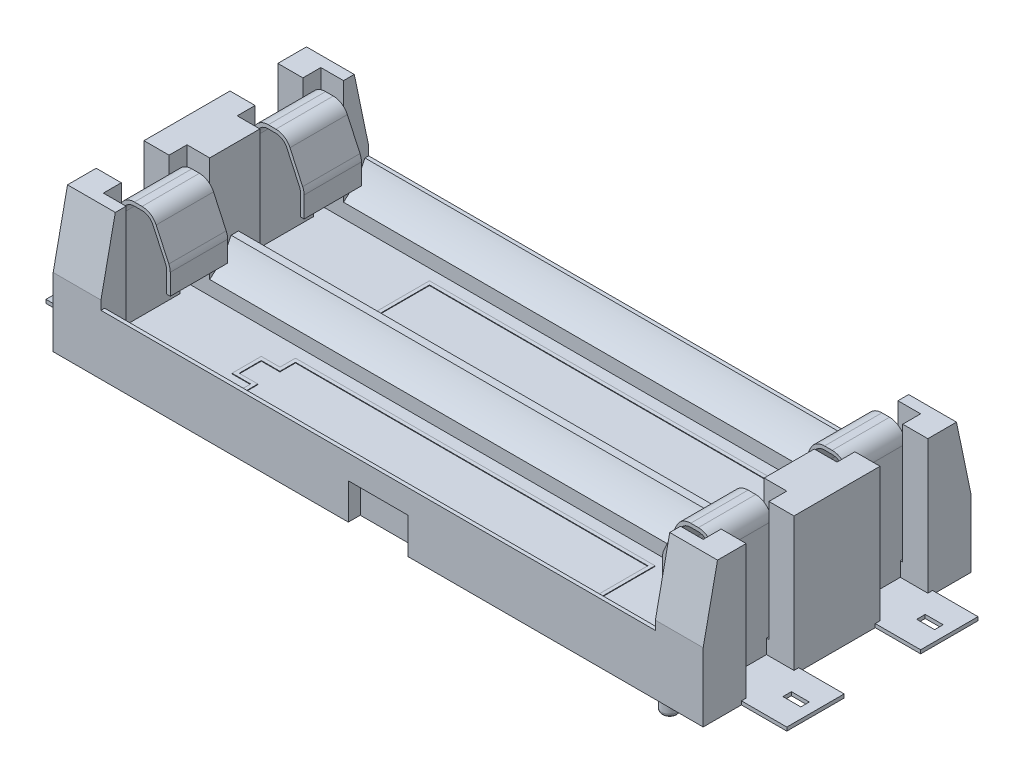
SolidWorks part; units mm, degrees
material "POM 乙缩醛共聚物"
ref_plane "Front" through (0, 0, 0) normal (0, 0, 1) x (1, 0, 0)
ref_plane "Top" through (0, 0, 0) normal (0, 1, 0) x (1, 0, 0)
ref_plane "Right" through (0, 0, 0) normal (1, 0, 0) x (0, 0, -1)
sketch "草图1" plane through (0, 0, 0) normal (0, 1, 0) x (1, 0, 0)
  line L1 (-27.2, -11.2) -> (27.2, -11.2)
  line L2 (-27.2, -11.2) -> (-27.2, 11.2)
  line L3 (-27.2, 11.2) -> (27.2, 11.2)
  line L4 (27.2, -11.2) -> (27.2, 11.2)
  line L5 (-27.2, -11.2) -> (27.2, 11.2) construction
  line L6 (-27.2, 11.2) -> (27.2, -11.2) construction
  point P0 (0, 0)
  dimension "D1" = 22.4
  dimension "D2" = 54.4
extrude "凸台-拉伸1" add sketch "草图1" along normal blind 11.5
ref_plane "基准面1" through (0, 5, 0) normal (0, 1, 0) x (1, 0, 0)
sketch "草图2" plane through (0, 5, 0) normal (0, 1, 0) x (1, 0, 0)
  line L1 (-23.2, -25.6311) -> (23.2, -25.6311)
  line L2 (-23.2, -25.6311) -> (-23.2, 25.6311)
  line L3 (-23.2, 25.6311) -> (23.2, 25.6311)
  line L4 (23.2, -25.6311) -> (23.2, 25.6311)
  line L5 (-23.2, -25.6311) -> (23.2, 25.6311) construction
  line L6 (-23.2, 25.6311) -> (23.2, -25.6311) construction
  point P0 (0, 0)
  dimension "D1" = 46.4
extrude "切除-拉伸1" cut sketch "草图2" along normal blind 11.4
sketch "草图3" plane through (0, 11.5, 0) normal (0, 1, 0) x (1, 0, 0)
  line L0 (-33.3126, 0) -> (0, 0) construction
  line L1 (0, 0) -> (0, 25.9446) construction
  line L2 (-23.2, 0) -> (-23.2, 11.2) construction
  line L3 (-23.2, 11.2) -> (-23.2, -11.2) construction
  line L4 (-27.2, 11.2) -> (-27.2, -11.2) construction
  line L5 (-21.3, 2.1) -> (-25.1, 2.1)
  line L6 (-21.3, 2.1) -> (-21.3, 9.1)
  line L7 (-21.3, 9.1) -> (-25.1, 9.1)
  line L8 (-25.1, 2.1) -> (-25.1, 3.6)
  line L9 (-21.3, 2.1) -> (-25.1, 9.1) construction
  line L10 (-21.3, 9.1) -> (-25.1, 2.1) construction
  line L11 (-25.1, 3.6) -> (-27.2, 3.6)
  line L14 (-27.2, 3.6) -> (-27.2, 7.6)
  line L15 (-23.2, 3.7905) -> (-27.2, 7.6) construction
  line L16 (-23.2, 7.4095) -> (-27.2, 3.6) construction
  line L17 (-25.1, 7.6) -> (-25.1, 9.1)
  line L18 (-25.1, 7.6) -> (-27.2, 7.6)
  line L19 (23.2, 7.4095) -> (27.2, 3.6) construction
  line L20 (23.2, 3.7905) -> (27.2, 7.6) construction
  line L21 (21.3, 9.1) -> (25.1, 2.1) construction
  line L22 (21.3, 2.1) -> (25.1, 9.1) construction
  line L23 (25.1, 7.6) -> (27.2, 7.6)
  line L24 (25.1, 7.6) -> (25.1, 9.1)
  line L25 (27.2, 3.6) -> (27.2, 7.6)
  line L26 (25.1, 3.6) -> (27.2, 3.6)
  line L27 (25.1, 2.1) -> (25.1, 3.6)
  line L28 (21.3, 9.1) -> (25.1, 9.1)
  line L29 (21.3, 2.1) -> (21.3, 9.1)
  line L30 (21.3, 2.1) -> (25.1, 2.1)
  line L31 (21.3, -2.1) -> (25.1, -9.1) construction
  line L32 (21.3, -9.1) -> (25.1, -2.1) construction
  line L33 (23.2, -3.7905) -> (27.2, -7.6) construction
  line L34 (23.2, -7.4095) -> (27.2, -3.6) construction
  line L35 (-23.2, -7.4095) -> (-27.2, -3.6) construction
  line L36 (-23.2, -3.7905) -> (-27.2, -7.6) construction
  line L37 (-21.3, -9.1) -> (-25.1, -2.1) construction
  line L38 (-21.3, -2.1) -> (-25.1, -9.1) construction
  line L39 (21.3, -2.1) -> (25.1, -2.1)
  line L40 (21.3, -2.1) -> (21.3, -9.1)
  line L41 (21.3, -9.1) -> (25.1, -9.1)
  line L42 (25.1, -2.1) -> (25.1, -3.6)
  line L43 (25.1, -3.6) -> (27.2, -3.6)
  line L44 (27.2, -3.6) -> (27.2, -7.6)
  line L45 (25.1, -7.6) -> (25.1, -9.1)
  line L46 (25.1, -7.6) -> (27.2, -7.6)
  line L47 (-25.1, -7.6) -> (-27.2, -7.6)
  line L48 (-25.1, -7.6) -> (-25.1, -9.1)
  line L49 (-27.2, -3.6) -> (-27.2, -7.6)
  line L50 (-25.1, -3.6) -> (-27.2, -3.6)
  line L51 (-25.1, -2.1) -> (-25.1, -3.6)
  line L52 (-21.3, -9.1) -> (-25.1, -9.1)
  line L53 (-21.3, -2.1) -> (-21.3, -9.1)
  line L54 (-21.3, -2.1) -> (-25.1, -2.1)
  point P9 (-23.2, 5.6)
  point P14 (-25.1, 5.6)
  point P33 (25.1, 5.6)
  point P34 (23.2, 5.6)
  point P55 (23.2, -5.6)
  point P56 (25.1, -5.6)
  point P57 (-25.1, -5.6)
  point P58 (-23.2, -5.6)
  dimension "D1" = 4
  dimension "D2" = 7
  dimension "D3" = 2.1
extrude "切除-拉伸2" cut sketch "草图3" against normal blind 10
sketch "草图4" plane through (-27.2, 0, 0) normal (-1, 0, 0) x (0, 0, 1)
  line L0 (0, 0) -> (0, 22.657) construction
  line L1 (-10, 11.5) -> (-11.2, 5.75)
  line L2 (-11.2, 11.5) -> (-7.6, 11.5) construction
  line L3 (-11.2, 11.5) -> (-11.2, 0) construction
  line L4 (-11.2, 5.75) -> (-14.7755, 5.75)
  line L5 (-14.7755, 5.75) -> (-14.7755, 11.5)
  line L6 (-14.7755, 11.5) -> (-10, 11.5)
  line L7 (14.7755, 11.5) -> (10, 11.5)
  line L8 (14.7755, 5.75) -> (14.7755, 11.5)
  line L9 (11.2, 5.75) -> (14.7755, 5.75)
  line L10 (10, 11.5) -> (11.2, 5.75)
  dimension "D1" = 10
extrude "切除-拉伸3" cut sketch "草图4" against normal through all
sketch "草图5" plane through (0, 1.5, 0) normal (0, 1, 0) x (1, 0, 0)
  line L0 (0, 23.9067) -> (0, 0) construction
  line L1 (0, 0) -> (-42.8753, 0) construction
  line L2 (24.6, 7.6) -> (24.6, 3.6)
  line L3 (-27.2, 7.6) -> (-24.6, 7.6)
  line L4 (-27.2, 7.6) -> (-27.2, 3.6)
  line L5 (-27.2, 3.6) -> (-24.6, 3.6)
  line L6 (-24.6, 7.6) -> (-24.6, 3.6)
  line L7 (27.2, 3.6) -> (24.6, 3.6)
  line L8 (27.2, 7.6) -> (27.2, 3.6)
  line L9 (27.2, 7.6) -> (24.6, 7.6)
  line L10 (27.2, -7.6) -> (24.6, -7.6)
  line L11 (27.2, -7.6) -> (27.2, -3.6)
  line L12 (27.2, -3.6) -> (24.6, -3.6)
  line L13 (-24.6, -7.6) -> (-24.6, -3.6)
  line L14 (-27.2, -3.6) -> (-24.6, -3.6)
  line L15 (-27.2, -7.6) -> (-27.2, -3.6)
  line L16 (-27.2, -7.6) -> (-24.6, -7.6)
  line L17 (24.6, -7.6) -> (24.6, -3.6)
  dimension "D1" = 2.6
extrude "切除-拉伸4" cut sketch "草图5" against normal blind 10
sketch "草图6" plane through (0, 1.5, 0) normal (0, 1, 0) x (1, 0, 0)
  line L0 (-21.3, 9.1) -> (-25.1, 9.1) construction
  line L1 (-21.8806, 9.1) -> (22.25, 9.1)
  line L2 (-21.8806, 9.1) -> (-21.8806, 2.1)
  line L3 (-21.8806, 2.1) -> (22.25, 2.1)
  line L4 (22.25, 9.1) -> (22.25, 2.1)
  line L5 (23.2, 2.1) -> (21.3, 2.1) construction
  line L6 (-23.2, -2.1) -> (-21.3, -2.1) construction
  line L7 (-22.25, -2.1) -> (22.25, -2.1)
  line L8 (-22.25, -2.1) -> (-22.25, -9.1)
  line L9 (-22.25, -9.1) -> (22.25, -9.1)
  line L10 (22.25, -2.1) -> (22.25, -9.1)
  line L11 (23.2, -9.1) -> (21.3, -9.1) construction
extrude "切除-拉伸5" cut sketch "草图6" along normal blind 10
sketch "草图7" plane through (0, 0, 0) normal (1, 0, 0) x (0, 0, -1)
  line L0 (-5.6, 1.5) -> (-5.6, 15.9161) construction
  line L1 (-7.6, 1.5) -> (-3.6, 1.5) construction
  line L2 (0, 0) -> (0, -3.0927) construction
  arc A0 (0, 8.5548) -> (0, 5.9452) centre (-5.6, 7.25) ccw
  circle A1 centre (-5.6, 7.25) radius 5.115 construction
  arc A2 (0, 8.5548) -> (0, 5.9452) centre (5.6, 7.25) cw
  dimension "D1" = 10.23
  dimension "D2" = 11.5
extrude "切除-拉伸6" cut sketch "草图7" against normal mid plane 46.4
sketch "草图8" plane through (0, 1.5, 0) normal (0, 1, 0) x (1, 0, 0)
  line L0 (-24.6, 5.6) -> (24.6, 5.6) construction
  line L1 (-24.6, 3.6) -> (-24.6, 7.6) construction
  line L2 (24.6, 7.6) -> (24.6, 3.6) construction
ref_plane "基准面2" through (0, 0, -5.6) normal (0, 0, 1) x (1, 0, 0)
sketch "草图9" plane through (0, 0, -5.6) normal (0, 0, 1) x (1, 0, 0)
  line L0 (-31, 0) -> (-24.6, 0)
  line L1 (-24.6, 0) -> (-24.6, 9.7542)
  line L2 (-23.6, 10.7542) -> (-22.9601, 10.7542)
  line L3 (-22.0522, 10.1735) -> (-20.9922, 7.8785)
  line L4 (-20.9, 7.4591) -> (-20.9, 5.7205)
  line L5 (-27.2, 0) -> (-27.2, 11.5) construction
  line L6 (-31, 0.3) -> (-24.9, 0.3)
  line L7 (-24.9, 0.3) -> (-24.9, 9.7542)
  line L8 (-23.6, 11.0542) -> (-22.9601, 11.0542)
  line L9 (-21.7799, 10.2993) -> (-20.7198, 8.0043)
  line L10 (-20.6, 7.4591) -> (-20.6, 5.7205)
  line L11 (-23.2, 2.6879) -> (-23.2, 11.5) construction
  line L12 (-20.9, 5.7205) -> (-20.6, 5.7205)
  line L13 (-20.6, 7.4591) -> (-20.6, 4.8223) construction
  line L14 (-20.9, 7.4591) -> (-20.9, 4.8223) construction
  line L15 (-31, 0.3) -> (-31, 0)
  arc A0 (-20.9, 7.4591) -> (-20.9922, 7.8785) centre (-21.9, 7.4591) ccw
  arc A1 (-24.6, 9.7542) -> (-23.6, 10.7542) centre (-23.6, 9.7542) cw
  arc A2 (-22.0522, 10.1735) -> (-22.9601, 10.7542) centre (-22.9601, 9.7542) ccw
  arc A3 (-24.9, 9.7542) -> (-23.6, 11.0542) centre (-23.6, 9.7542) cw
  arc A4 (-21.7799, 10.2993) -> (-22.9601, 11.0542) centre (-22.9601, 9.7542) ccw
  arc A5 (-20.6, 7.4591) -> (-20.7198, 8.0043) centre (-21.9, 7.4591) ccw
  point P27 (-20.9, 6.5898)
  dimension "D1" = 1
  dimension "D2" = 3.8
  dimension "D4" = 2.3
  dimension "D3" = 0.3
extrude "凸台-拉伸2" add sketch "草图9" along normal mid plane 4.8 separate body
sketch "草图10" plane through (0, 0.3, 0) normal (0, 1, 0) x (1, 0, 0)
  line L0 (-31, 5.6) -> (-24.9913, 5.6) construction
  line L1 (-31, 3.2) -> (-31, 8) construction
  line L2 (-27.06, 5.6) -> (27.06, 5.6) construction
  line L4 (-30.1262, 5.2434) -> (-28.6276, 5.2434)
  line L5 (-30.1262, 5.2434) -> (-30.1262, 5.9566)
  line L6 (-30.1262, 5.9566) -> (-28.6276, 5.9566)
  line L7 (-28.6276, 5.2434) -> (-28.6276, 5.9566)
  line L8 (-30.1262, 5.2434) -> (-28.6276, 5.9566) construction
  line L9 (-30.1262, 5.9566) -> (-28.6276, 5.2434) construction
  point P7 (-29.3769, 5.6)
extrude "切除-拉伸7" cut sketch "草图10" against normal blind 4.8
mirror "镜向2" about plane through (0, 0, 0) normal (1, 0, 0) of "切除-拉伸7", "凸台-拉伸2"
mirror "镜向6" about plane through (0, 0, 0) normal (0, 0, 1)
fillet "圆角1" radius 1 5 edges at (-27.2, 11.5, -8.8) (-27.2, 11.5, 8.8) (27.2, 11.5, -8.8) (27.2, 11.5, 0) (27.2, 11.5, 8.8)
mirror "镜向7" about plane through (0, 0, 0) normal (0, 0, 1) of "切除-拉伸7", "凸台-拉伸2"
sketch "草图11" plane through (0, 1.5, 0) normal (0, 1, 0) x (1, 0, 0)
  line L0 (14.7474, 6.5392) -> (14.7474, 7.8392)
  line L1 (-14.7474, 3.394) -> (14.7474, 3.394)
  line L2 (-14.7474, 3.394) -> (-14.7474, 7.8392)
  line L3 (-14.7474, 7.8392) -> (14.7474, 7.8392)
  line L4 (14.7474, 3.394) -> (14.7474, 4.694)
  line L5 (-14.7474, 3.394) -> (14.7474, 7.8392) construction
  line L6 (-14.7474, 7.8392) -> (14.7474, 3.394) construction
  line L7 (14.7474, 6.5392) -> (16.3092, 6.5392)
  line L9 (14.7474, 4.694) -> (16.3092, 4.694)
  line L10 (16.3092, 6.5392) -> (16.3092, 4.694)
  line L11 (-15.0474, 8.1392) -> (15.0474, 8.1392)
  line L12 (15.0474, 6.8392) -> (15.0474, 8.1392)
  line L13 (15.0474, 6.8392) -> (16.6092, 6.8392)
  line L14 (16.6092, 6.8392) -> (16.6092, 4.394)
  line L15 (15.0474, 4.394) -> (16.6092, 4.394)
  line L16 (15.0474, 3.094) -> (15.0474, 4.394)
  line L17 (-15.0474, 3.094) -> (15.0474, 3.094)
  line L18 (-15.0474, 3.094) -> (-15.0474, 8.1392)
  line L19 (-14.7474, -6.5206) -> (-14.7474, -7.8206)
  line L20 (14.7474, -3.3754) -> (-14.7474, -3.3754)
  line L21 (14.7474, -3.3754) -> (14.7474, -7.8206)
  line L22 (14.7474, -7.8206) -> (-14.7474, -7.8206)
  line L23 (-14.7474, -3.3754) -> (-14.7474, -4.6754)
  line L24 (14.7474, -3.3754) -> (-14.7474, -7.8206) construction
  line L25 (14.7474, -7.8206) -> (-14.7474, -3.3754) construction
  line L26 (-14.7474, -6.5206) -> (-16.3092, -6.5206)
  line L27 (-14.7474, -4.6754) -> (-16.3092, -4.6754)
  line L28 (-16.3092, -6.5206) -> (-16.3092, -4.6754)
  line L29 (15.0474, -8.1206) -> (-15.0474, -8.1206)
  line L30 (-15.0474, -6.8206) -> (-15.0474, -8.1206)
  line L31 (-15.0474, -6.8206) -> (-16.6092, -6.8206)
  line L32 (-16.6092, -6.8206) -> (-16.6092, -4.3754)
  line L33 (-15.0474, -4.3754) -> (-16.6092, -4.3754)
  line L34 (-15.0474, -3.0754) -> (-15.0474, -4.3754)
  line L35 (15.0474, -3.0754) -> (-15.0474, -3.0754)
  line L36 (15.0474, -3.0754) -> (15.0474, -8.1206)
  point P0 (0, 5.6166)
  point P17 (0, -5.598)
  dimension "D1" = 1.3
  dimension "D2" = 1.3
  dimension "D4" = 1.3
  dimension "D5" = 1.3
  dimension "D3" = 0.3
extrude "凸台-拉伸3" add sketch "草图11" along normal blind 0.05
sketch "草图12" plane through (0, 0, 0) normal (0, -1, 0) x (1, 0, 0)
  line L0 (0, 14.8855) -> (0, 0) construction
  line L1 (0, 0) -> (-21.2951, 0) construction
  line L2 (27.2, 11.2) -> (-27.2, 11.2) construction
  line L3 (-2.5, 19.571) -> (2.5, 19.571)
  line L4 (-2.5, 19.571) -> (-2.5, 10.2)
  line L5 (-2.5, 10.2) -> (2.5, 10.2)
  line L6 (2.5, 19.571) -> (2.5, 10.2)
  line L7 (-2.5, 19.571) -> (2.5, 10.2) construction
  line L8 (-2.5, 10.2) -> (2.5, 19.571) construction
  line L9 (-2.5, -10.2) -> (2.5, -19.571) construction
  line L10 (-2.5, -19.571) -> (2.5, -10.2) construction
  line L11 (2.5, -19.571) -> (2.5, -10.2)
  line L12 (-2.5, -10.2) -> (2.5, -10.2)
  line L13 (-2.5, -19.571) -> (-2.5, -10.2)
  line L14 (-2.5, -19.571) -> (2.5, -19.571)
  dimension "D1" = 5
  dimension "D2" = 1
extrude "切除-拉伸8" cut sketch "草图12" against normal blind 3
sketch "草图13" plane through (0, 0, 0) normal (0, -1, 0) x (1, 0, 0)
  line L0 (2.5, 10.2) -> (2.5, 11.2) construction
  line L1 (27.2, 11.2) -> (2.5, 11.2) construction
  circle A0 centre (23.5, 10.31) radius 0.66
  dimension "D2" = 1.32
  dimension "D1" = 21
  dimension "D3" = 0.89
extrude "凸台-拉伸4" add sketch "草图13" along normal blind 1.2
fillet "圆角2" radius 0.3 1 edges at (23.5, -1.2, 9.65)
